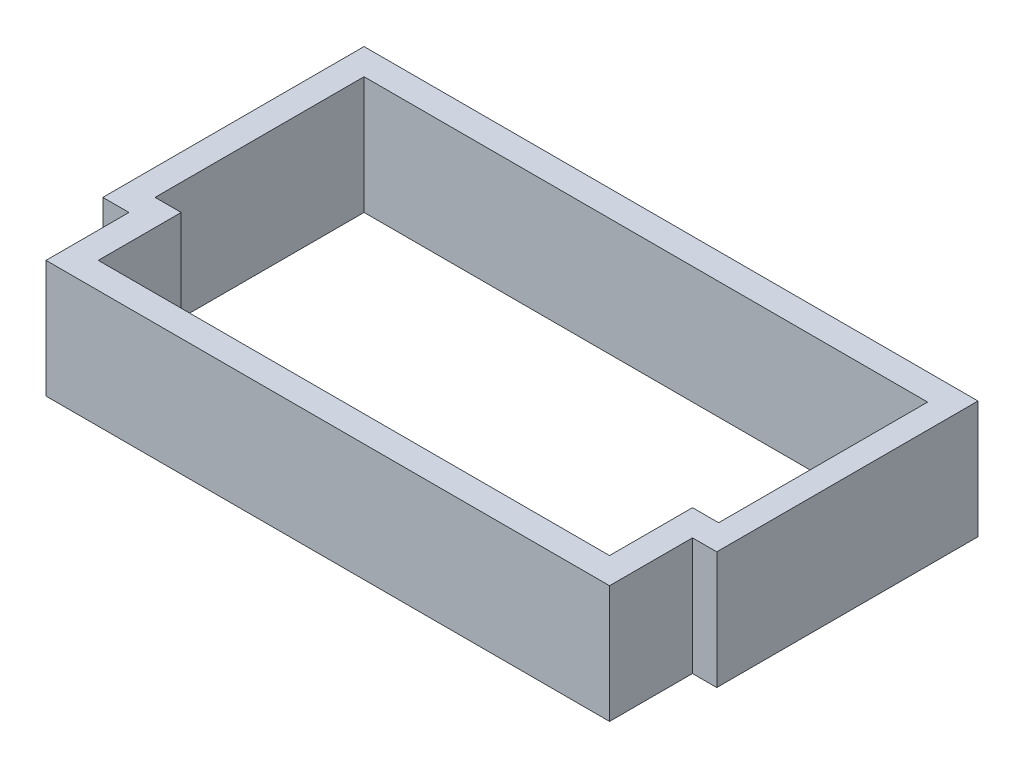
SolidWorks part; units mm, degrees
ref_plane "Front Plane" through (0, 0, 0) normal (0, 0, 1) x (1, 0, 0)
ref_plane "Top Plane" through (0, 0, 0) normal (0, 1, 0) x (1, 0, 0)
ref_plane "Right Plane" through (0, 0, 0) normal (1, 0, 0) x (0, 0, -1)
sketch "Sketch1" plane through (0, 0, 0) normal (0, 1, 0) x (1, 0, 0)
  line L0 (0, 4) -> (0, -4) construction
  line L1 (11.7144, 5) -> (11.7144, -5)
  line L4 (10.7856, 4) -> (10.7856, -4)
  line L5 (11.7144, 5) -> (-11.7856, 5)
  line L6 (-10.7856, 4) -> (10.7856, 4)
  line L7 (10.7856, -4) -> (9.7856, -4)
  line L8 (-11.7856, -5) -> (-10.7856, -5)
  line L9 (-10.7856, -4) -> (-10.7856, 4)
  line L10 (-11.7856, 5) -> (-11.7856, -5)
  line L11 (9.7856, -4) -> (9.7856, -7.175)
  line L12 (10.7856, 0) -> (-10.7856, 0) construction
  line L15 (11.7144, -5) -> (10.7856, -5)
  line L16 (-9.7856, -4) -> (-9.7856, -7.175)
  line L17 (-9.7856, -7.175) -> (9.7856, -7.175)
  line L19 (-9.7856, -4) -> (-10.7856, -4)
  line L22 (10.7856, -8.175) -> (10.7856, -5)
  line L24 (-10.7856, -5) -> (-10.7856, -8.175)
  line L25 (-10.7856, -8.175) -> (10.7856, -8.175)
  line L27 (9.7856, -7.175) -> (9.7856, -5) construction
  line L28 (-9.7856, -5) -> (-9.7856, -7.175) construction
  dimension "D1" = 1
extrude "Boss-Extrude1" add sketch "Sketch1" along normal blind 4.5
ref_plane "Plane1" through (0, 0, 15) normal (0, 0, 1) x (1, 0, 0)
sketch "Sketch3" plane through (0, 0, 15) normal (0, 0, 1) x (1, 0, 0)
  line L1 (-8.5, 9.5) -> (8.5, 9.5)
  line L2 (-8.5, 9.5) -> (-8.5, 15)
  line L3 (-8.5, 15) -> (8.5, 15)
  line L4 (8.5, 9.5) -> (8.5, 15)
  dimension "D1" = 8.5
  dimension "D2" = 8.5
  dimension "D3" = 15
  dimension "D4" = 9.5
sketch "Sketch4" plane through (0, 4.5, 0) normal (0, 1, 0) x (1, 0, 0)
  line L4 (-11.7856, -5) -> (-10.7856, -5)
  line L5 (11.7144, 5) -> (-11.7856, 5)
  line L6 (-11.7856, 5) -> (-11.7856, -5)
  line L7 (-11.7856, -5) -> (-10.7856, -5)
  line L8 (-10.7856, -5) -> (-10.7856, -8.175)
  line L9 (11.7144, 5) -> (-11.7856, 5)
  line L10 (-11.7856, 5) -> (-11.7856, -5)
  line L11 (-10.7856, -5) -> (-10.7856, -8.175)
  line L16 (-10.7856, -8.175) -> (10.7856, -8.175)
  line L17 (-10.7856, -8.175) -> (10.7856, -8.175)
  line L18 (10.7856, -8.175) -> (10.7856, -5)
  line L19 (10.7856, -8.175) -> (10.7856, -5)
  line L20 (10.7856, -5) -> (11.7144, -5)
  line L21 (10.7856, -5) -> (11.7144, -5)
  line L22 (11.7144, -5) -> (11.7144, 5)
  line L23 (11.7144, -5) -> (11.7144, 5)
  dimension "D1" = 0
sketch "Sketch5" plane through (0, 0, 0) normal (1, 0, 0) x (0, 0, -1)
  line L0 (-15, 9.5) -> (-15, 15) construction
  line L1 (-15, 9.5) -> (-15, 15) construction
  line L2 (-22.925, 12.1) -> (-8.3574, 12.1) construction
  arc A0 (-5, 4.5) -> (-15, 11.8721) centre (-17.1413, -1.5009) ccw
sketch "Sketch6" plane through (0, 0, 0) normal (1, 0, 0) x (0, 0, -1)
  line L2 (5, 4.5) -> (0.3531, 11.1714)
  line L3 (0.3531, 11.1714) -> (-7.6055, 14.2744)
  line L4 (-7.6055, 14.2744) -> (-15, 15)
  line L5 (-15, 9.5) -> (-15, 15) construction
  line L6 (-15, 9.5) -> (-15, 15) construction
